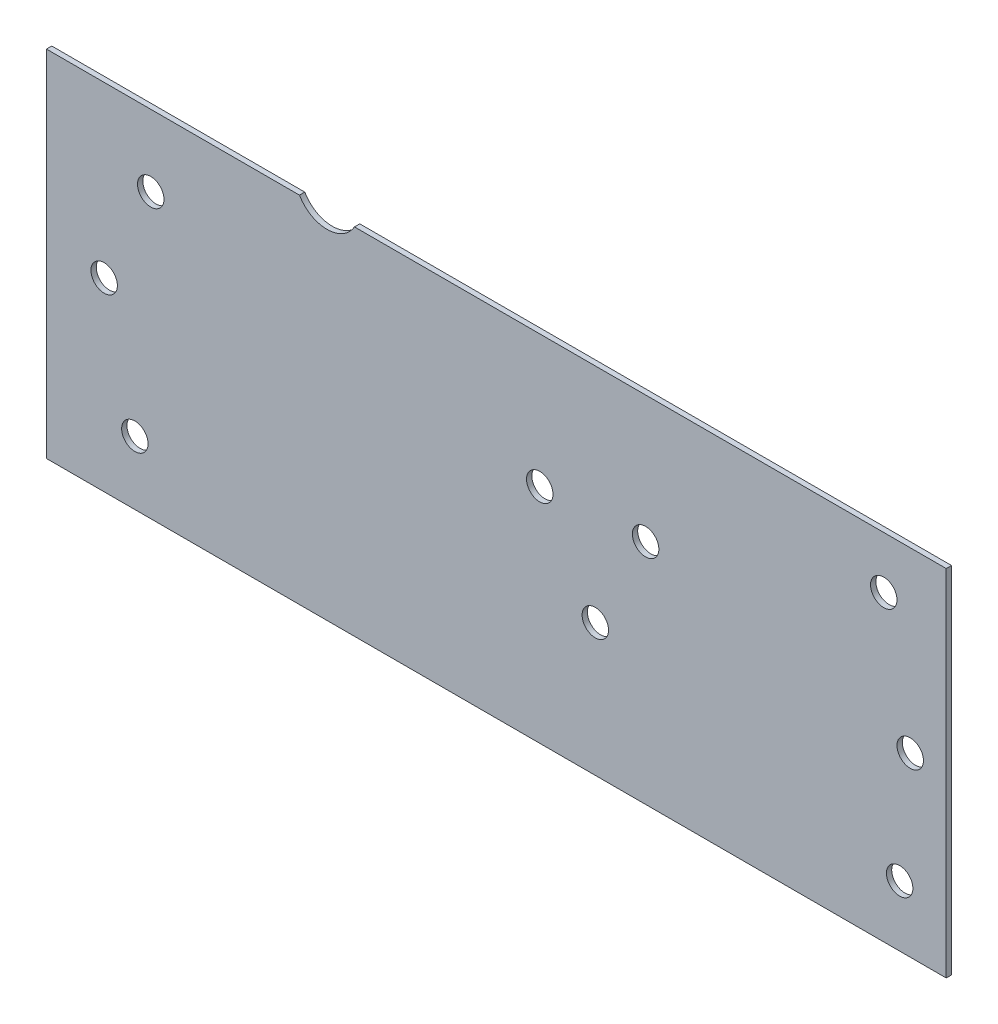
SolidWorks part; units mm, degrees
ref_plane "Front Plane" through (0, 0, 0) normal (0, 0, 1) x (1, 0, 0)
ref_plane "Top Plane" through (0, 0, 0) normal (0, 1, 0) x (1, 0, 0)
ref_plane "Right Plane" through (0, 0, 0) normal (1, 0, 0) x (0, 0, -1)
sketch "Sketch1" plane through (0, 0, 0) normal (0, 0, 1) x (1, 0, 0)
  line L0 (-32, 36.5) -> (-32, 30.5)
  line L1 (91, -33.5) -> (-88.5, -33.5) construction
  line L2 (-85, -33.5) -> (85, -33.5)
  line L3 (-85, -33.5) -> (-85, 33.5)
  line L4 (-85, 33.5) -> (85, 33.5)
  line L5 (85, -33.5) -> (85, 33.5)
  circle A0 centre (8.2, 8.5) radius 2.5
  circle A1 centre (28.2, 9.5) radius 2.5
  circle A2 centre (18.7, -8.5) radius 2.5
  circle A3 centre (73.2, 23.7) radius 2.5
  circle A4 centre (78.2, -0.1) radius 2.5
  circle A5 centre (76.2, -22) radius 2.5
  circle A6 centre (-68.3, -21.5) radius 2.5
  circle A7 centre (-74.1, 1.5) radius 2.5
  circle A8 centre (-65.3, 20) radius 2.5
  circle A10 centre (-32, 36.5) radius 6
  circle A16 centre (28.2, 9.5) radius 2.5 construction
  point P36 (-32, 33.5)
  point P44 (0, 33.5)
  dimension "D3" = 12
  dimension "D1" = 170
  dimension "D2" = 53
  dimension "D4" = 67
extrude "Boss-Extrude1" add sketch "Sketch1" along normal blind 1 contours A10 L4 L3 L2 L5 A8 A7 A6 A5 A4 A3 A2 A1 A0
